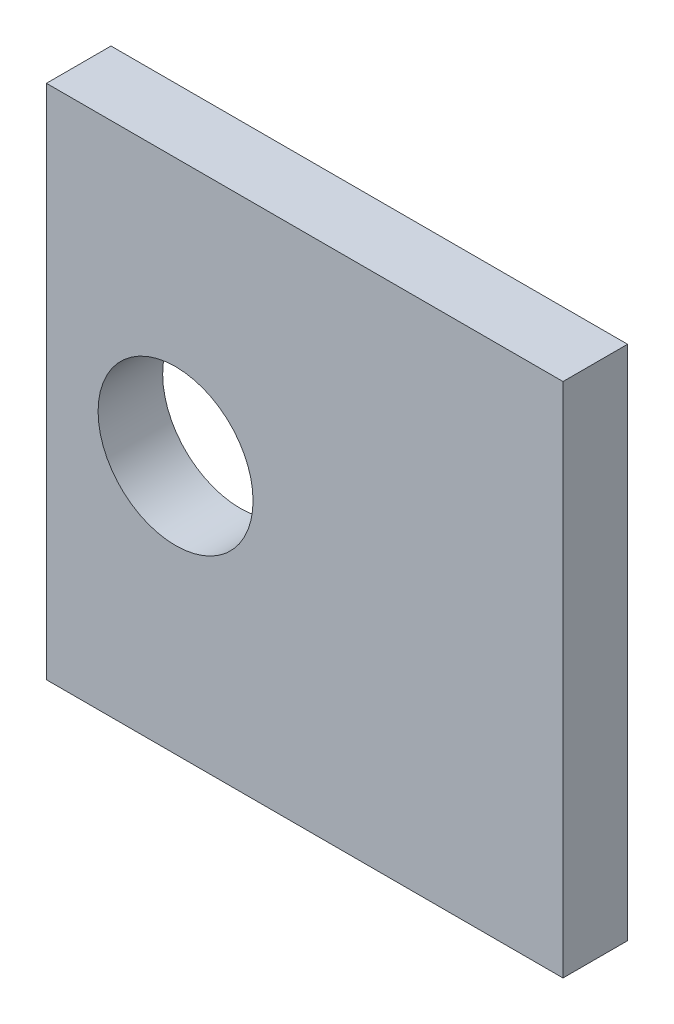
SolidWorks part; units mm, degrees
ref_plane "Front Plane" through (0, 0, 0) normal (0, 0, 1) x (1, 0, 0)
ref_plane "Top Plane" through (0, 0, 0) normal (0, 1, 0) x (1, 0, 0)
ref_plane "Right Plane" through (0, 0, 0) normal (1, 0, 0) x (0, 0, -1)
sketch "Sketch1" plane through (0, 0, 0) normal (0, 0, 1) x (1, 0, 0)
  line L1 (20, 20) -> (-20, 20)
  line L2 (20, 20) -> (20, -20)
  line L3 (20, -20) -> (-20, -20)
  line L4 (-20, 20) -> (-20, -20)
  line L5 (20, 20) -> (-20, -20) construction
  line L6 (20, -20) -> (-20, 20) construction
  circle A0 centre (-10, 0) radius 6
  point P0 (0, 0)
  dimension "D1" = 12
  dimension "D2" = 40
  dimension "D3" = 40
  dimension "D4" = 10
extrude "Boss-Extrude1" add sketch "Sketch1" along normal blind 5
